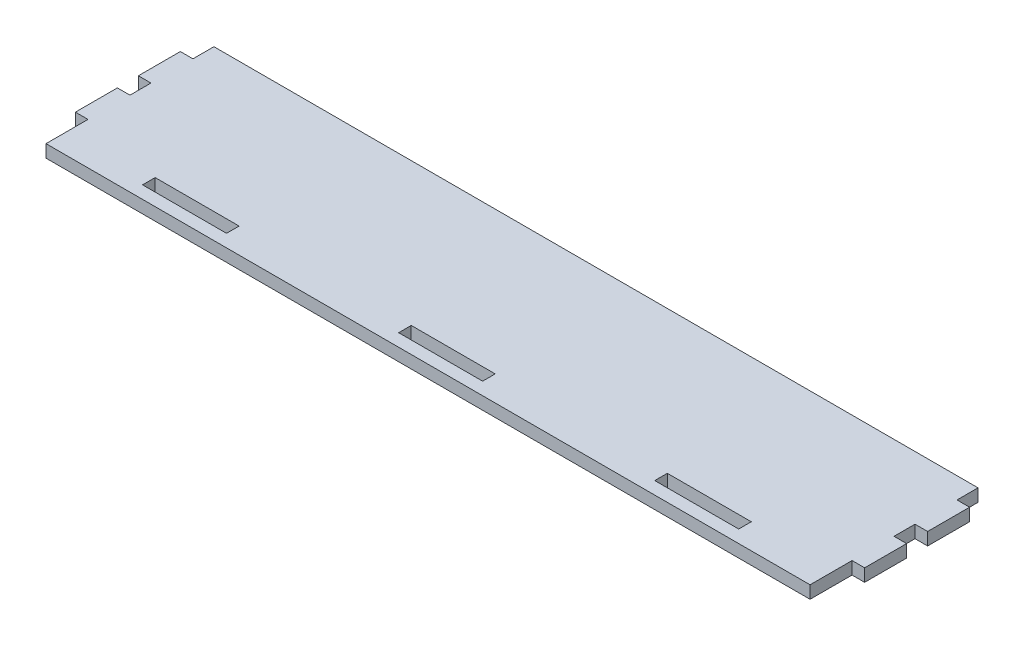
SolidWorks part; units mm, degrees
material "ABS"
ref_plane "Front Plane" through (0, 0, 0) normal (0, 0, 1) x (1, 0, 0)
ref_plane "Top Plane" through (0, 0, 0) normal (0, 1, 0) x (1, 0, 0)
ref_plane "Right Plane" through (0, 0, 0) normal (1, 0, 0) x (0, 0, -1)
sketch "Sketch1" plane through (0, 0, 0) normal (0, 1, 0) x (1, 0, 0)
  line L0 (0, 35) -> (0, 40)
  line L1 (0, 0) -> (182, 0)
  line L2 (0, 0) -> (0, 10)
  line L3 (0, 40) -> (182, 40)
  line L4 (182, 0) -> (182, 10)
  line L5 (182, 35) -> (185, 35)
  line L7 (182, 25) -> (185, 25)
  line L8 (185, 35) -> (185, 25)
  line L9 (182, 20) -> (185, 20)
  line L11 (182, 10) -> (185, 10)
  line L12 (185, 20) -> (185, 10)
  line L13 (0, 35) -> (-3, 35)
  line L15 (0, 25) -> (-3, 25)
  line L16 (-3, 35) -> (-3, 25)
  line L17 (0, 20) -> (-3, 20)
  line L19 (0, 10) -> (-3, 10)
  line L20 (-3, 20) -> (-3, 10)
  line L21 (0, 20) -> (0, 25)
  line L22 (182, 35) -> (182, 40)
  line L23 (182, 20) -> (182, 25)
  line L25 (20, 6) -> (40, 6)
  line L26 (20, 6) -> (20, 3)
  line L27 (20, 3) -> (40, 3)
  line L28 (40, 6) -> (40, 3)
  line L29 (142, 6) -> (162, 6)
  line L30 (142, 6) -> (142, 3)
  line L31 (142, 3) -> (162, 3)
  line L32 (162, 6) -> (162, 3)
  line L33 (81, 6) -> (101, 6)
  line L34 (81, 6) -> (81, 3)
  line L35 (81, 3) -> (101, 3)
  line L36 (101, 6) -> (101, 3)
  point P21 (-1.5, 35)
  point P34 (0, 5)
  dimension "D1" = 182
  dimension "D2" = 40
  dimension "D3" = 3
  dimension "D4" = 3
  dimension "D5" = 10
  dimension "D6" = 10
  dimension "D7" = 5
  dimension "D8" = 10
  dimension "D9" = 10
  dimension "D10" = 10
  dimension "D11" = 3
  dimension "D12" = 3
  dimension "D13" = 10
  dimension "D14" = 5
  dimension "D15" = 20
  dimension "D16" = 20
  dimension "D17" = 20
  dimension "D18" = 3
  dimension "D19" = 3
  dimension "D20" = 3
  dimension "D21" = 20
  dimension "D22" = 41
  dimension "D23" = 20
  dimension "D24" = 3
  dimension "D25" = 3
  dimension "D26" = 3
extrude "Boss-Extrude1" add sketch "Sketch1" along normal blind 3
